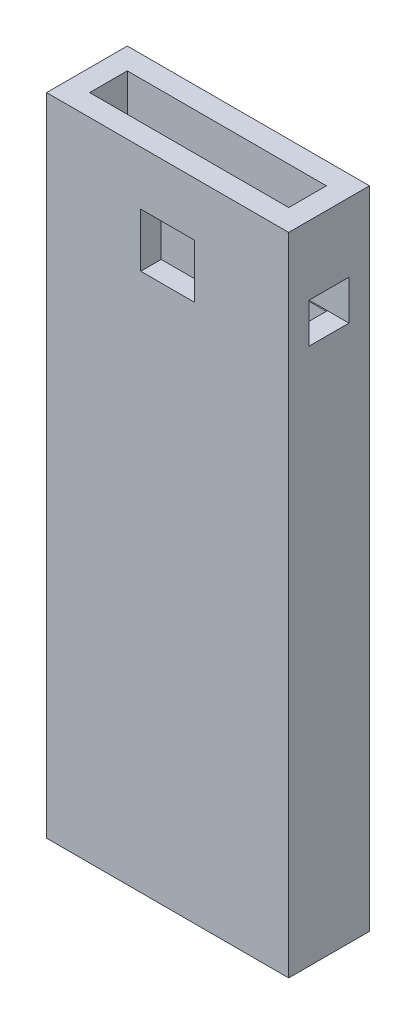
SolidWorks part; units mm, degrees
ref_plane "Front Plane" through (0, 0, 0) normal (0, 0, 1) x (1, 0, 0)
ref_plane "Top Plane" through (0, 0, 0) normal (0, 1, 0) x (1, 0, 0)
ref_plane "Right Plane" through (0, 0, 0) normal (1, 0, 0) x (0, 0, -1)
sketch "Sketch1" plane through (0, 0, 0) normal (0, 1, 0) x (1, 0, 0)
  line L1 (22.5, -7.5) -> (-22.5, -7.5)
  line L2 (22.5, -7.5) -> (22.5, 7.5)
  line L3 (22.5, 7.5) -> (-22.5, 7.5)
  line L4 (-22.5, -7.5) -> (-22.5, 7.5)
  line L5 (22.5, -7.5) -> (-22.5, 7.5) construction
  line L6 (22.5, 7.5) -> (-22.5, -7.5) construction
  point P0 (0, 0)
  dimension "D1" = 45
  dimension "D2" = 15
extrude "Boss-Extrude1" add sketch "Sketch1" along normal mid plane 120
shell "Shell1" thickness 4
sketch "Sketch3" plane through (0, -60, 0) normal (0, -1, 0) x (1, 0, 0)
  line L1 (5, -3.5) -> (-5, -3.5)
  line L2 (5, -3.5) -> (5, 3.5)
  line L3 (5, 3.5) -> (-5, 3.5)
  line L4 (-5, -3.5) -> (-5, 3.5)
  line L5 (5, -3.5) -> (-5, 3.5) construction
  line L6 (5, 3.5) -> (-5, -3.5) construction
  point P0 (0, 0)
  dimension "D1" = 10
  dimension "D2" = 7
extrude "Cut-Extrude2" cut sketch "Sketch3" against normal blind 4
sketch "Sketch4" plane through (0, 0, 7.5) normal (0, 0, 1) x (1, 0, 0)
  line L0 (0, -8.25) -> (0, 8.25) construction
  line L1 (5, 50) -> (-5, 50)
  line L2 (5, 50) -> (5, 40)
  line L3 (5, 40) -> (-5, 40)
  line L4 (-5, 50) -> (-5, 40)
  line L5 (5, 50) -> (-5, 40) construction
  line L6 (5, 40) -> (-5, 50) construction
  line L7 (-22.5, 60) -> (22.5, 60) construction
  point P0 (0, 45)
  dimension "D1" = 10
  dimension "D2" = 10
extrude "Cut-Extrude3" cut sketch "Sketch4" against normal up to next
sketch "Sketch5" plane through (22.5, 0, 0) normal (1, 0, 0) x (0, 0, -1)
  line L0 (0, 24.75) -> (0, -24.75) construction
  line L1 (3.7, 39.8) -> (-3.7, 39.8)
  line L2 (3.7, 39.8) -> (3.7, 47.2)
  line L3 (3.7, 47.2) -> (-3.7, 47.2)
  line L4 (-3.7, 39.8) -> (-3.7, 47.2)
  line L5 (3.7, 39.8) -> (-3.7, 47.2) construction
  line L6 (3.7, 47.2) -> (-3.7, 39.8) construction
  line L7 (-7.5, 60) -> (7.5, 60) construction
  point P0 (0, 43.5)
  dimension "D1" = 20.2
  dimension "D2" = 7.4
  dimension "D3" = 7.4
extrude "Cut-Extrude4" cut sketch "Sketch5" against normal through all
sketch "Sketch6" plane through (0, -60, 0) normal (0, -1, 0) x (1, 0, 0)
  line L0 (24.75, 0) -> (-24.75, 0) construction
  line L1 (-15, 4.2724) -> (-18.7, 2.1362)
  line L2 (-18.7, 2.1362) -> (-18.7, -2.1362)
  line L3 (-18.7, -2.1362) -> (-15, -4.2724)
  line L4 (-15, -4.2724) -> (-11.3, -2.1362)
  line L5 (-11.3, -2.1362) -> (-11.3, 2.1362)
  line L6 (-11.3, 2.1362) -> (-15, 4.2724)
  line L7 (0, -7.5) -> (0, 7.5) construction
  line L8 (22.5, -7.5) -> (-22.5, -7.5) construction
  line L9 (-22.5, 7.5) -> (22.5, 7.5) construction
  line L10 (11.3, 2.1362) -> (15, 4.2724)
  line L11 (11.3, -2.1362) -> (11.3, 2.1362)
  line L12 (15, -4.2724) -> (11.3, -2.1362)
  line L13 (18.7, -2.1362) -> (15, -4.2724)
  line L14 (18.7, 2.1362) -> (18.7, -2.1362)
  line L15 (15, 4.2724) -> (18.7, 2.1362)
  circle A0 centre (-15, 0) radius 3.7 construction
  circle A1 centre (15, 0) radius 3.7 construction
  dimension "D1" = 7.4
  dimension "D2" = 30
extrude "Cut-Extrude5" cut sketch "Sketch6" against normal blind 3.6 from offset 1.2 offset against normal yes
sketch "Sketch7" plane through (0, -60, 0) normal (0, -1, 0) x (1, 0, 0)
  line L0 (24.75, 0) -> (-24.75, 0) construction
  line L1 (0, 7.5) -> (0, -7.5) construction
  line L2 (-22.5, 7.5) -> (22.5, 7.5) construction
  line L3 (22.5, -7.5) -> (-22.5, -7.5) construction
  circle A0 centre (-15, 0) radius 2.1
  circle A1 centre (15, 0) radius 2.1
  dimension "D1" = 4.2
  dimension "D2" = 30
extrude "Cut-Extrude6" cut sketch "Sketch7" against normal through all
